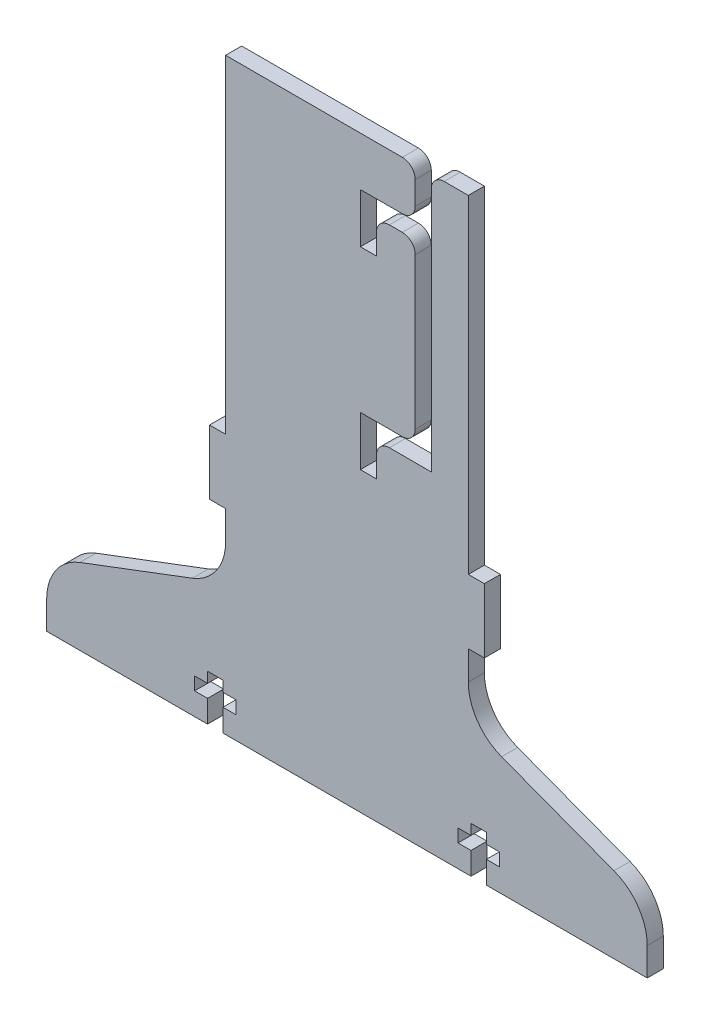
SolidWorks part; units mm, degrees
ref_plane "Front Plane" through (0, 0, 0) normal (0, 0, 1) x (1, 0, 0)
ref_plane "Top Plane" through (0, 0, 0) normal (0, 1, 0) x (1, 0, 0)
ref_plane "Right Plane" through (0, 0, 0) normal (1, 0, 0) x (0, 0, -1)
sketch "Sketch1" plane through (0, 0, 0) normal (0, 0, 1) x (1, 0, 0)
  line L0 (4.4701, 71.0138) -> (4.4701, 36.0888)
  line L1 (-12.7, 0) -> (12.7, 0)
  line L2 (-12.7, 0) -> (-12.7, 83.8378)
  line L3 (-12.7, 83.8378) -> (4.4701, 83.8378)
  line L4 (12.7, 0) -> (12.7, 83.8378)
  line L5 (7.6451, 83.8378) -> (12.7, 83.8378)
  line L6 (-6.35, 71.0138) -> (-6.35, 64.4098)
  line L7 (-6.35, 64.4098) -> (-3.175, 64.4098)
  line L8 (-3.175, 71.0138) -> (-3.175, 64.4098)
  line L9 (-3.175, 71.0138) -> (4.4701, 71.0138)
  line L10 (-6.35, 71.0138) -> (-6.35, 74.1888)
  line L11 (-6.35, 74.1888) -> (4.4701, 74.1888)
  line L13 (7.6451, 32.9138) -> (-3.175, 32.9138)
  line L14 (4.4701, 83.8378) -> (4.4701, 74.1888)
  line L16 (7.6451, 83.8378) -> (7.6451, 32.9138)
  line L18 (4.4701, 36.0888) -> (-6.35, 36.0888)
  line L19 (-6.35, 32.9138) -> (-6.35, 36.0888)
  line L21 (-6.35, 32.9138) -> (-6.35, 26.3098)
  line L22 (-6.35, 26.3098) -> (-3.175, 26.3098)
  line L23 (-3.175, 32.9138) -> (-3.175, 26.3098)
  dimension "D1" = 83.8378
  dimension "D2" = 3.175
  dimension "D4" = 6.604
  dimension "D5" = 3.175
  dimension "D6" = 25.4
  dimension "D7" = 3.175
  dimension ".125" = 3.175
  dimension "D8" = 6.604
  dimension "D9" = 3.175
  dimension "D10" = 38.1
extrude "Boss-Extrude1" add sketch "Sketch1" along normal blind 3.175
sketch "Sketch2" plane through (0, 0, 0) normal (0, 0, 1) x (1, 0, 0)
  line L1 (12.7, 0) -> (18.1267, 0)
  line L2 (12.7, 0) -> (12.7, 83.8378)
  line L3 (12.7, 83.8378) -> (18.1267, 83.8378)
  line L4 (18.1267, 0) -> (18.1267, 83.8378)
  line L5 (-12.7, 83.8378) -> (-36.1244, 83.8378)
  line L6 (-12.7, 83.8378) -> (-12.7, 0)
  line L7 (-12.7, 0) -> (-36.1244, 0)
  line L8 (-36.1244, 83.8378) -> (-36.1244, 0)
  dimension "D1" = 5.4267
  dimension "D2" = 23.4244
extrude "Boss-Extrude2" add sketch "Sketch2" along normal blind 3.175
sketch "Sketch3" plane through (0, 0, 0) normal (0, 0, 1) x (1, 0, 0)
  line L0 (18.1267, 0) -> (18.1267, 83.8378) construction
  line L1 (-36.1244, 83.8378) -> (-32.9494, 83.8378)
  line L2 (-36.1244, 83.8378) -> (-36.1244, 19.05)
  line L3 (-36.1244, 19.05) -> (-32.9494, 19.05)
  line L4 (-32.9494, 83.8378) -> (-32.9494, 19.05)
  line L5 (18.1267, 19.05) -> (14.9517, 19.05)
  line L6 (18.1267, 19.05) -> (18.1267, 83.8378)
  line L7 (18.1267, 83.8378) -> (14.9517, 83.8378)
  line L8 (14.9517, 19.05) -> (14.9517, 83.8378)
  line L9 (4.4701, 83.8378) -> (-36.1244, 83.8378) construction
  line L10 (-36.1244, 0) -> (18.1267, 0) construction
  line L12 (-36.1244, 0) -> (-32.9494, 0)
  line L13 (-36.1244, 0) -> (-36.1244, 6.35)
  line L14 (-36.1244, 6.35) -> (-32.9494, 6.35)
  line L15 (-32.9494, 0) -> (-32.9494, 6.35)
  line L16 (18.1267, 0) -> (14.9517, 0)
  line L17 (18.1267, 0) -> (18.1267, 6.35)
  line L18 (18.1267, 6.35) -> (14.9517, 6.35)
  line L19 (14.9517, 0) -> (14.9517, 6.35)
  dimension "D1" = 19.05
  dimension "D2" = 3.175
  dimension "D3" = 6.35
extrude "Cut-Extrude2" cut sketch "Sketch3" along normal through all
sketch "Sketch4" plane through (0, 0, 3.175) normal (0, 0, 1) x (1, 0, 0)
  line L0 (-12.9946, 19.0693) -> (-12.9946, 38.2214) construction
  line L1 (-20.6339, 19.0693) -> (-20.6339, 38.2214)
  line L2 (-5.3553, 19.0693) -> (-5.3553, 38.2214)
  arc A0 (-20.6339, 19.0693) -> (-5.3553, 19.0693) centre (-12.9946, 19.0693) ccw
  arc A1 (-5.3553, 38.2214) -> (-20.6339, 38.2214) centre (-12.9946, 38.2214) ccw
  point P2 (-12.9946, 28.6453)
extrude "Cut-Extrude3" [suppressed] cut sketch "Sketch4" against normal through all
sketch "Sketch5" plane through (0, 0, 0) normal (0, 0, 1) x (1, 0, 0)
  line L0 (-32.9494, 0) -> (-32.9494, -6.35)
  line L1 (-32.9494, -6.35) -> (-68.268, -19.7171)
  line L2 (-68.268, -19.7171) -> (-68.268, -32.2821)
  line L3 (-68.268, -32.2821) -> (50.2703, -32.2821)
  line L4 (50.2703, -32.2821) -> (50.2703, -19.7171)
  line L5 (50.2703, -19.7171) -> (14.9517, -6.35)
  line L6 (14.9517, -6.35) -> (14.9517, 0)
  line L7 (-32.9494, 0) -> (14.9517, 0)
  dimension "D1" = 12.5649
  dimension "D2" = 13.3671
  dimension "D3" = 6.35
extrude "Boss-Extrude4" add sketch "Sketch5" along normal blind 3.175
fillet "Fillet1" radius 10.16 4 edges at (14.9517, -6.35, 1.5875) (-32.9494, -6.35, 1.5875) (50.2703, -19.7171, 1.5875) (-68.268, -19.7171, 1.5875)
sketch "Sketch6" plane through (0, 0, 0) normal (0, 0, 1) x (1, 0, 0)
  line L0 (-68.268, -32.2821) -> (50.2703, -32.2821) construction
  line L2 (50.2703, -32.2821) -> (50.2703, -26.7352) construction
  point P0 (50.2703, -29.5086)
  line B0 (-36.518, -32.2821) -> (-36.518, -27.8707)
  line B1 (-36.518, -27.8707) -> (-39.0765, -27.8707)
  line B2 (-39.0765, -27.8707) -> (-39.0765, -25.3122)
  line B3 (-39.0765, -25.3122) -> (-36.518, -25.3122)
  line B4 (-36.518, -25.3122) -> (-36.518, -23.2334)
  line B5 (-36.518, -23.2334) -> (-33.4798, -23.2334)
  line B6 (-33.4798, -23.2334) -> (-33.4798, -25.3122)
  line B7 (-33.4798, -25.3122) -> (-30.9213, -25.3122)
  line B8 (-30.9213, -25.3122) -> (-30.9213, -27.8707)
  line B9 (-30.9213, -27.8707) -> (-33.4798, -27.8707)
  line B10 (-33.4798, -27.8707) -> (-33.4798, -32.2821)
  line B11 (-33.4798, -32.2821) -> (-36.518, -32.2821)
  line B12 (15.4821, -32.2821) -> (15.4821, -27.8707)
  line B13 (15.4821, -27.8707) -> (12.9236, -27.8707)
  line B14 (12.9236, -27.8707) -> (12.9236, -25.3122)
  line B15 (12.9236, -25.3122) -> (15.4821, -25.3122)
  line B16 (15.4821, -25.3122) -> (15.4821, -23.2334)
  line B17 (15.4821, -23.2334) -> (18.5203, -23.2334)
  line B18 (18.5203, -23.2334) -> (18.5203, -25.3122)
  line B19 (18.5203, -25.3122) -> (21.0788, -25.3122)
  line B20 (21.0788, -25.3122) -> (21.0788, -27.8707)
  line B21 (21.0788, -27.8707) -> (18.5203, -27.8707)
  line B22 (18.5203, -27.8707) -> (18.5203, -32.2821)
  line B23 (18.5203, -32.2821) -> (15.4821, -32.2821)
  dimension "D1" = 31.75
  dimension "D2" = 31.75
sketch_block_instance "Block1-1"
sketch_block "Block1"
sketch_block_instance "Block1-2"
extrude "Cut-Extrude5" cut sketch "Sketch6" along normal through all
fillet "Fillet2" radius 2.54 7 edges at (4.4701, 36.0888, 1.5875) (-3.175, 32.9138, 1.5875) (7.6451, 83.8378, 1.5875) (4.4701, 83.8378, 1.5875) (-3.175, 71.0138, 1.5875) (4.4701, 71.0138, 1.5875) (4.4701, 74.1888, 1.5875)
